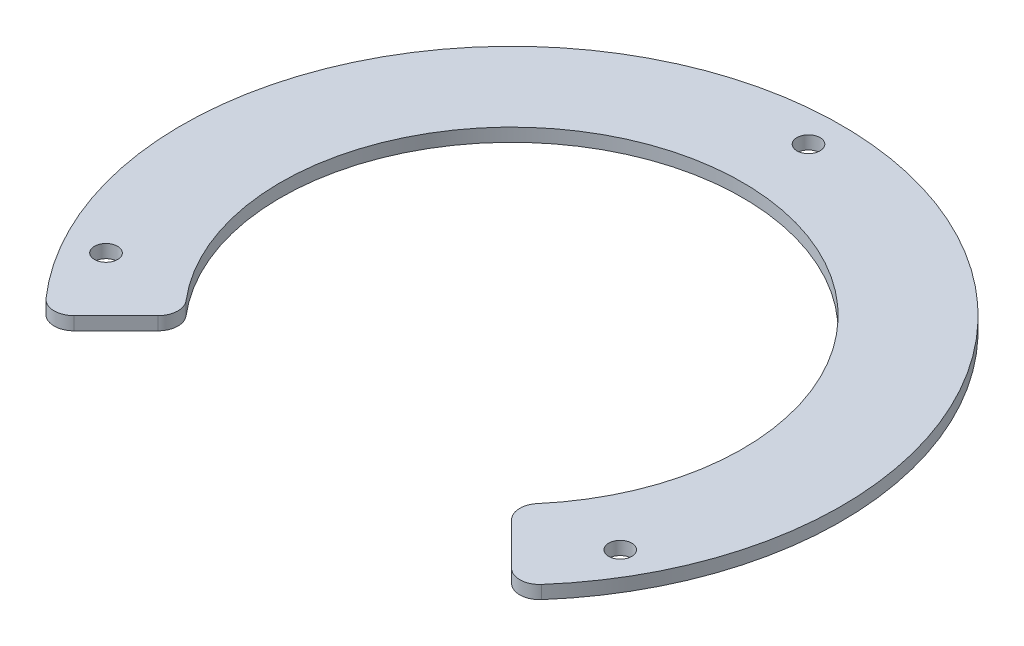
SolidWorks part; units mm, degrees
ref_plane "Front Plane" through (0, 0, 0) normal (0, 0, 1) x (1, 0, 0)
ref_plane "Top Plane" through (0, 0, 0) normal (0, 1, 0) x (1, 0, 0)
ref_plane "Right Plane" through (0, 0, 0) normal (1, 0, 0) x (0, 0, -1)
sketch "Sketch1" plane through (0, 0, 0) normal (0, 1, 0) x (1, 0, 0)
  circle A0 centre (0, 0) radius 35
  circle A1 centre (0, 0) radius 50
  circle A2 centre (0, 0) radius 45 construction
  circle A3 centre (0, 45) radius 1.75
  circle A4 centre (38.9711, -22.5) radius 1.75
  circle A5 centre (-38.9711, -22.5) radius 1.75
  point P13 (0, 0)
  dimension "D1" = 70
  dimension "D2" = 100
  dimension "D3" = 90
  dimension "D4" = 3.5
  dimension "D5" = 3
extrude "Boss-Extrude1" add sketch "Sketch1" along normal blind 2
sketch "Sketch2" plane through (0, 2, 0) normal (0, 1, 0) x (1, 0, 0)
  line L0 (0, 0) -> (-50, -50)
  line L5 (-50, -50) -> (50, -50)
  line L6 (50, -50) -> (0, 0)
  circle A0 centre (0, 0) radius 35 construction
  circle A1 centre (0, 0) radius 50 construction
  point P0 (0, -35)
  dimension "D1" = 90
extrude "Cut-Extrude1" cut sketch "Sketch2" against normal blind 14
fillet "Fillet1" radius 3 4 edges at (-24.7487, 1, 24.7487) (-35.3553, 1, 35.3553) (35.3553, 1, 35.3553) (24.7487, 1, 24.7487)
